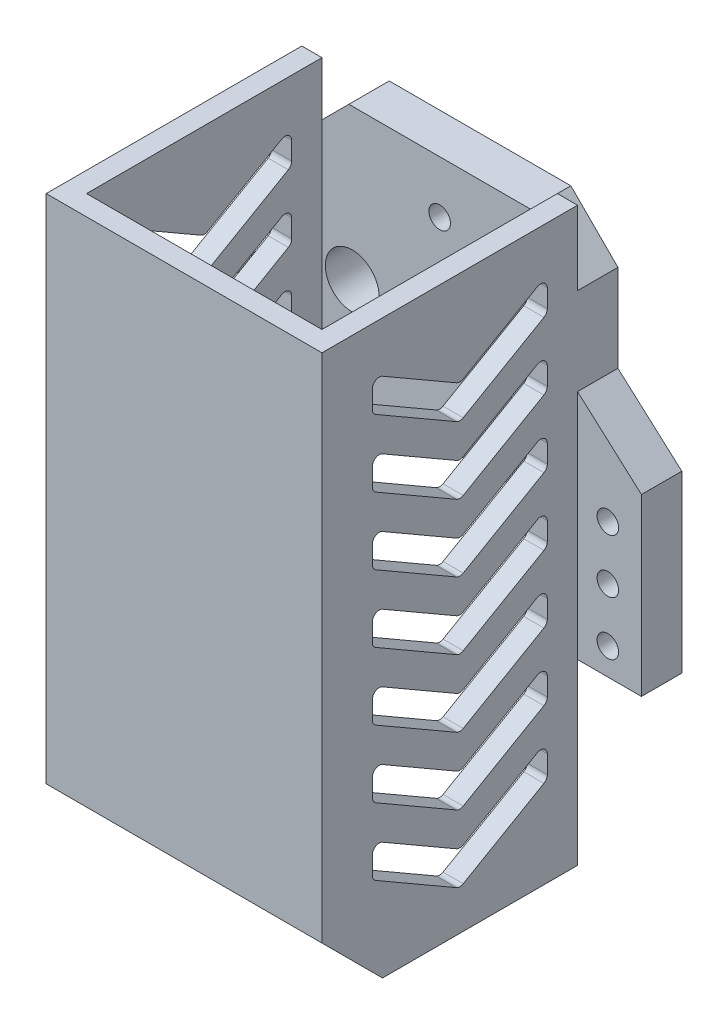
SolidWorks part; units mm, degrees
material "ABS"
ref_plane "前视基准面" through (0, 0, 0) normal (0, 0, 1) x (1, 0, 0)
ref_plane "上视基准面" through (0, 0, 0) normal (0, 1, 0) x (1, 0, 0)
ref_plane "右视基准面" through (0, 0, 0) normal (1, 0, 0) x (0, 0, -1)
sketch "草图1" plane through (0, 0, 0) normal (0, 0, 1) x (1, 0, 0)
  line L0 (0, 0) -> (0, -121.3935) construction
  line L1 (-30, -83.5) -> (-17.5, -83.5)
  line L2 (-30, -57.5) -> (-30, -85.5) construction
  line L3 (-30, -83.5) -> (-30, -57.5)
  line L6 (-13.5, -29) -> (13.5, -29)
  line L9 (30, -57.5) -> (30, -83.5)
  line L10 (30, -85.5) -> (30, -57.5) construction
  line L11 (30, -83.5) -> (17.5, -83.5)
  line L12 (17.5, -83.5) -> (17.5, -66)
  line L13 (17.5, -66) -> (-17.5, -66)
  line L14 (-17.5, -66) -> (-17.5, -83.5)
  line L15 (-20.5, -36) -> (-20.5, -49)
  line L16 (-20.5, -49) -> (-30, -57.5)
  line L17 (20.5, -36) -> (20.5, -49)
  line L18 (20.5, -49) -> (30, -57.5)
  line L19 (-13.5, -29) -> (-20.5, -36)
  line L20 (13.5, -29) -> (20.5, -36)
  circle A0 centre (-25, -63.5) radius 1.6
  circle A1 centre (-25, -71.5) radius 1.6
  circle A2 centre (-25, -79.5) radius 1.6
  circle A3 centre (25, -63.5) radius 1.6
  circle A4 centre (25, -71.5) radius 1.6
  circle A5 centre (25, -79.5) radius 1.6
  circle A6 centre (13, -51.5) radius 4
  circle A7 centre (-13, -51.5) radius 4
  circle A8 centre (-10, -60.5) radius 1.6
  circle A9 centre (10, -60.5) radius 1.6
  circle A10 centre (0, -36.8) radius 1.6
  point P12 (20.5, -29)
  point P14 (-20.5, -29)
  dimension "D7" = 3.2
  dimension "D10" = 3.2
  dimension "D11" = 3.2
  dimension "D12" = 3.2
  dimension "D13" = 3.2
  dimension "D14" = 3.2
  dimension "D15" = 8
  dimension "D16" = 8
  dimension "D17" = 3.2
  dimension "D18" = 3.2
  dimension "D19" = 3.2
  dimension "D1" = 20.5
  dimension "D2" = 29
  dimension "D3" = 20
  dimension "D4" = 26
  dimension "D5" = 3
  dimension "D6" = 37
extrude "凸台-拉伸1" add sketch "草图1" along normal blind 6
sketch "草图2" plane through (0, 0, 6) normal (0, 0, 1) x (1, 0, 0)
  line L0 (-17.5, -110) -> (-17.5, -25)
  line L1 (-20.5, -25) -> (-17.5, -25)
  line L3 (-20.5, -25) -> (-20.5, -110)
  line L4 (0, 0) -> (0, -12.358) construction
  line L12 (20.5, -110) -> (17.5, -110)
  line L13 (-17.5, -83.5) -> (-17.5, -66) construction
  line L14 (-20.5, -110) -> (-17.5, -110)
  line L16 (-20.5, -36) -> (-20.5, -49) construction
  line L17 (20.5, -25) -> (20.5, -110)
  line L18 (20.5, -25) -> (17.5, -25)
  line L19 (17.5, -110) -> (17.5, -25)
  dimension "D1" = 85
  dimension "D3" = 25
extrude "凸台-拉伸2" add sketch "草图2" along normal blind 35
sketch "草图5" plane through (20.5, 0, 0) normal (1, 0, 0) x (0, 0, -1)
  line L0 (-23.5, -25) -> (-23.5, -110) construction
  line L3 (-36, -96.9378) -> (-24, -103.866)
  line L4 (-23, -103.866) -> (-11, -96.9378)
  line L5 (-10.5, -96.0718) -> (-10.5, -93.3812)
  line L6 (-12, -92.5152) -> (-23, -98.866)
  line L7 (-24, -98.866) -> (-35, -92.5152)
  line L8 (-36.5, -93.3812) -> (-36.5, -96.0718)
  line L9 (-36, -86.9378) -> (-24, -93.866)
  line L10 (-23, -93.866) -> (-11, -86.9378)
  line L11 (-10.5, -86.0718) -> (-10.5, -83.3812)
  line L12 (-12, -82.5152) -> (-23, -88.866)
  line L13 (-24, -88.866) -> (-35, -82.5152)
  line L14 (-36.5, -83.3812) -> (-36.5, -86.0718)
  line L15 (-36, -76.9378) -> (-24, -83.866)
  line L16 (-23, -83.866) -> (-11, -76.9378)
  line L17 (-10.5, -76.0718) -> (-10.5, -73.3812)
  line L18 (-12, -72.5152) -> (-23, -78.866)
  line L19 (-24, -78.866) -> (-35, -72.5152)
  line L20 (-36.5, -73.3812) -> (-36.5, -76.0718)
  line L21 (-36, -66.9378) -> (-24, -73.866)
  line L22 (-23, -73.866) -> (-11, -66.9378)
  line L23 (-10.5, -66.0718) -> (-10.5, -63.3812)
  line L24 (-12, -62.5152) -> (-23, -68.866)
  line L25 (-24, -68.866) -> (-35, -62.5152)
  line L26 (-36.5, -63.3812) -> (-36.5, -66.0718)
  line L27 (-36, -56.9378) -> (-24, -63.866)
  line L28 (-23, -63.866) -> (-11, -56.9378)
  line L29 (-10.5, -56.0718) -> (-10.5, -53.3812)
  line L30 (-12, -52.5152) -> (-23, -58.866)
  line L31 (-24, -58.866) -> (-35, -52.5152)
  line L32 (-36.5, -53.3812) -> (-36.5, -56.0718)
  line L33 (-36, -46.9378) -> (-24, -53.866)
  line L34 (-23, -53.866) -> (-11, -46.9378)
  line L35 (-10.5, -46.0718) -> (-10.5, -43.3812)
  line L36 (-12, -42.5152) -> (-23, -48.866)
  line L37 (-24, -48.866) -> (-35, -42.5152)
  line L38 (-36.5, -43.3812) -> (-36.5, -46.0718)
  line L39 (-36, -36.9378) -> (-24, -43.866)
  line L40 (-23, -43.866) -> (-11, -36.9378)
  line L41 (-10.5, -36.0718) -> (-10.5, -33.3812)
  line L42 (-12, -32.5152) -> (-23, -38.866)
  line L43 (-24, -38.866) -> (-35, -32.5152)
  line L44 (-36.5, -33.3812) -> (-36.5, -36.0718)
  line L47 (-41, -110) -> (-6, -110) construction
  line L48 (-41, -25) -> (-6, -25) construction
  arc A0 (-11, -96.9378) -> (-10.5, -96.0718) centre (-11.5, -96.0718) ccw
  arc A1 (-10.5, -93.3812) -> (-12, -92.5152) centre (-11.5, -93.3812) ccw
  arc A2 (-35, -92.5152) -> (-36.5, -93.3812) centre (-35.5, -93.3812) ccw
  arc A3 (-36, -96.9378) -> (-36.5, -96.0718) centre (-35.5, -96.0718) cw
  arc A4 (-24, -103.866) -> (-23, -103.866) centre (-23.5, -103) ccw
  arc A5 (-23, -98.866) -> (-24, -98.866) centre (-23.5, -98) cw
  arc A6 (-11, -86.9378) -> (-10.5, -86.0718) centre (-11.5, -86.0718) ccw
  arc A7 (-10.5, -83.3812) -> (-12, -82.5152) centre (-11.5, -83.3812) ccw
  arc A8 (-35, -82.5152) -> (-36.5, -83.3812) centre (-35.5, -83.3812) ccw
  arc A9 (-36, -86.9378) -> (-36.5, -86.0718) centre (-35.5, -86.0718) cw
  arc A10 (-24, -93.866) -> (-23, -93.866) centre (-23.5, -93) ccw
  arc A11 (-23, -88.866) -> (-24, -88.866) centre (-23.5, -88) cw
  arc A12 (-11, -76.9378) -> (-10.5, -76.0718) centre (-11.5, -76.0718) ccw
  arc A13 (-10.5, -73.3812) -> (-12, -72.5152) centre (-11.5, -73.3812) ccw
  arc A14 (-35, -72.5152) -> (-36.5, -73.3812) centre (-35.5, -73.3812) ccw
  arc A15 (-36, -76.9378) -> (-36.5, -76.0718) centre (-35.5, -76.0718) cw
  arc A16 (-24, -83.866) -> (-23, -83.866) centre (-23.5, -83) ccw
  arc A17 (-23, -78.866) -> (-24, -78.866) centre (-23.5, -78) cw
  arc A18 (-11, -66.9378) -> (-10.5, -66.0718) centre (-11.5, -66.0718) ccw
  arc A19 (-10.5, -63.3812) -> (-12, -62.5152) centre (-11.5, -63.3812) ccw
  arc A20 (-35, -62.5152) -> (-36.5, -63.3812) centre (-35.5, -63.3812) ccw
  arc A21 (-36, -66.9378) -> (-36.5, -66.0718) centre (-35.5, -66.0718) cw
  arc A22 (-24, -73.866) -> (-23, -73.866) centre (-23.5, -73) ccw
  arc A23 (-23, -68.866) -> (-24, -68.866) centre (-23.5, -68) cw
  arc A24 (-11, -56.9378) -> (-10.5, -56.0718) centre (-11.5, -56.0718) ccw
  arc A25 (-10.5, -53.3812) -> (-12, -52.5152) centre (-11.5, -53.3812) ccw
  arc A26 (-35, -52.5152) -> (-36.5, -53.3812) centre (-35.5, -53.3812) ccw
  arc A27 (-36, -56.9378) -> (-36.5, -56.0718) centre (-35.5, -56.0718) cw
  arc A28 (-24, -63.866) -> (-23, -63.866) centre (-23.5, -63) ccw
  arc A29 (-23, -58.866) -> (-24, -58.866) centre (-23.5, -58) cw
  arc A30 (-11, -46.9378) -> (-10.5, -46.0718) centre (-11.5, -46.0718) ccw
  arc A31 (-10.5, -43.3812) -> (-12, -42.5152) centre (-11.5, -43.3812) ccw
  arc A32 (-35, -42.5152) -> (-36.5, -43.3812) centre (-35.5, -43.3812) ccw
  arc A33 (-36, -46.9378) -> (-36.5, -46.0718) centre (-35.5, -46.0718) cw
  arc A34 (-24, -53.866) -> (-23, -53.866) centre (-23.5, -53) ccw
  arc A35 (-23, -48.866) -> (-24, -48.866) centre (-23.5, -48) cw
  arc A36 (-11, -36.9378) -> (-10.5, -36.0718) centre (-11.5, -36.0718) ccw
  arc A37 (-10.5, -33.3812) -> (-12, -32.5152) centre (-11.5, -33.3812) ccw
  arc A38 (-35, -32.5152) -> (-36.5, -33.3812) centre (-35.5, -33.3812) ccw
  arc A39 (-36, -36.9378) -> (-36.5, -36.0718) centre (-35.5, -36.0718) cw
  arc A40 (-24, -43.866) -> (-23, -43.866) centre (-23.5, -43) ccw
  arc A41 (-23, -38.866) -> (-24, -38.866) centre (-23.5, -38) cw
  point P18 (-36.5, -91.6491)
  point P21 (-36.5, -96.6491)
  point P24 (-23.5, -104.1547)
  point P27 (-23.5, -99.1547)
  point P30 (-23.5, -104)
  dimension "D7" = 1
  dimension "D8" = 1
  dimension "D3" = 6
  dimension "D1" = 60
  dimension "D2" = 60
  dimension "D4" = 13
  dimension "D5" = 13
  dimension "D6" = 5
  dimension "D9" = 7
extrude "切除-拉伸2" cut sketch "草图5" against normal through all
sketch "草图7" plane through (0, 0, 0) normal (0, 0, -1) x (-1, 0, 0)
  circle A0 centre (10, -60.5) radius 3
  circle A1 centre (-10, -60.5) radius 3
  circle A2 centre (0, -36.8) radius 3
  dimension "D1" = 6
  dimension "D2" = 6
  dimension "D3" = 6
extrude "切除-拉伸4" cut sketch "草图7" against normal blind 3
sketch "草图8" plane through (0, 0, 41) normal (0, 0, 1) x (1, 0, 0)
  line L0 (-20.5, -25) -> (20.5, -25)
  line L1 (20.5, -25) -> (20.5, -110)
  line L2 (20.5, -110) -> (-20.5, -110)
  line L3 (-20.5, -110) -> (-20.5, -25)
extrude "凸台-拉伸3" add sketch "草图8" along normal blind 3
sketch "草图9" plane through (20.5, 0, 0) normal (1, 0, 0) x (0, 0, -1)
  line L0 (-44, -110) -> (-44, -101)
  line L1 (-44, -110) -> (-44, -25) construction
  line L2 (-44, -101) -> (-35, -110)
  line L3 (-44, -110) -> (-6, -110) construction
  line L4 (-35, -110) -> (-44, -110)
  dimension "D1" = 9
  dimension "D2" = 9
extrude "切除-拉伸5" cut sketch "草图9" against normal up to next
